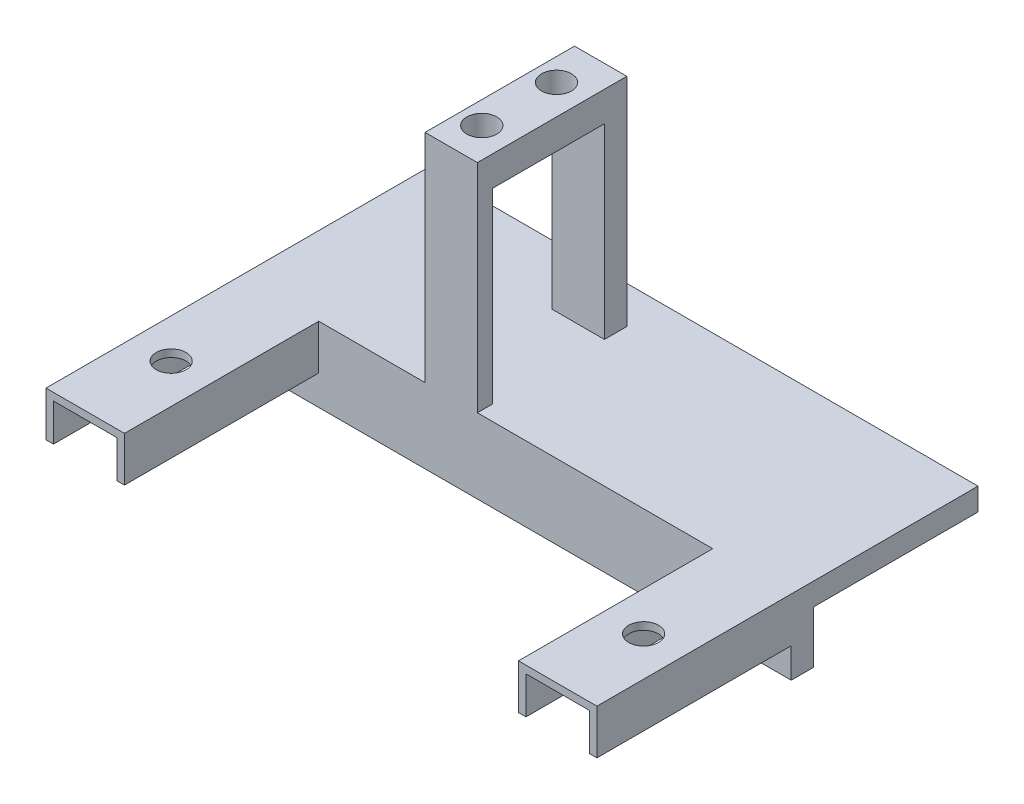
SolidWorks part; units mm, degrees
ref_plane "Front Plane" through (0, 0, 0) normal (0, 0, 1) x (1, 0, 0)
ref_plane "Top Plane" through (0, 0, 0) normal (0, 1, 0) x (1, 0, 0)
ref_plane "Right Plane" through (0, 0, 0) normal (1, 0, 0) x (0, 0, -1)
sketch "Sketch1" plane through (0, 0, 0) normal (0, 0, 1) x (1, 0, 0)
  line L1 (0, 0) -> (73.73, 0)
  line L2 (0, 0) -> (0, 10)
  line L3 (0, 10) -> (73.73, 10)
  line L4 (73.73, 0) -> (73.73, 10)
  dimension "D1" = 73.73
  dimension "D2" = 10
extrude "Boss-Extrude1" add sketch "Sketch1" along normal blind 3
sketch "Sketch2" plane through (0, 0, 3) normal (0, 0, 1) x (1, 0, 0)
  line L0 (0, 4) -> (0, 10)
  line L1 (0, 10) -> (0, 0) construction
  line L2 (0, 10) -> (10.5, 10)
  line L3 (73.73, 10) -> (0, 10) construction
  line L4 (10.5, 10) -> (10.5, 4)
  line L5 (10.5, 4) -> (9.5, 4)
  line L6 (9.5, 4) -> (9.5, 9)
  line L7 (9.5, 9) -> (1, 9)
  line L8 (1, 9) -> (1, 4)
  line L9 (1, 4) -> (0, 4)
  dimension "D1" = 1
  dimension "D2" = 1
  dimension "D3" = 6
  dimension "D4" = 6
  dimension "D5" = 1
  dimension "D6" = 10.5
extrude "Boss-Extrude2" add sketch "Sketch2" along normal blind 26
sketch "Sketch7" plane through (0, 0, 3) normal (0, 0, 1) x (1, 0, 0)
  line L0 (-2.8767, 4) -> (79.6378, 4) construction
  line L1 (73.73, 10) -> (73.73, 4)
  line L2 (73.73, 0) -> (73.73, 10) construction
  line L3 (73.73, 4) -> (72.73, 4)
  line L4 (72.73, 4) -> (72.73, 9)
  line L5 (72.73, 9) -> (64.23, 9)
  line L6 (64.23, 9) -> (64.23, 4)
  line L7 (64.23, 4) -> (63.23, 4)
  line L8 (63.23, 4) -> (63.23, 10)
  line L9 (73.73, 10) -> (10.5, 10) construction
  line L10 (63.23, 10) -> (73.73, 10)
  dimension "D1" = 1
  dimension "D2" = 1
  dimension "D3" = 1
  dimension "D4" = 10.5
extrude "Boss-Extrude3" add sketch "Sketch7" along normal blind 26
sketch "Sketch8" plane through (0, 10, 0) normal (0, 1, 0) x (1, 0, 0)
  line L0 (5.25, -29) -> (5.25, -34.0804) construction
  line L1 (10.5, -29) -> (0, -29) construction
  line L2 (5.25, -34.0804) -> (5.25, 6.4511) construction
  line L3 (68.48, -29) -> (68.48, -34.7376) construction
  line L4 (73.73, -29) -> (63.23, -29) construction
  line L5 (68.48, -34.7376) -> (68.48, 5.4901) construction
  circle A0 centre (5.25, -17.5) radius 2
  circle A1 centre (68.48, -17.5) radius 2
  dimension "D2" = 4
  dimension "D4" = 4
  dimension "D1" = 11.5
  dimension "D3" = 11.5
extrude "Cut-Extrude1" cut sketch "Sketch8" against normal through all
sketch "Sketch10" plane through (0, 0, 0) normal (0, 0, -1) x (-1, 0, 0)
  line L0 (0, 10) -> (0, 0) construction
  line L1 (-73.73, 10) -> (0, 10)
  line L2 (-73.73, 10) -> (-73.73, 7)
  line L3 (-73.73, 7) -> (0, 7)
  line L4 (0, 10) -> (0, 7)
  dimension "D1" = 3
extrude "Boss-Extrude4" add sketch "Sketch10" along normal blind 22
sketch "Sketch11" plane through (0, 10, 0) normal (0, 1, 0) x (1, 0, 0)
  line L0 (63.23, -3) -> (10.5, -3) construction
  line L1 (24.73, -3) -> (31.73, -3)
  line L2 (24.73, -3) -> (24.73, 17)
  line L3 (24.73, 17) -> (31.73, 17)
  line L4 (31.73, -3) -> (31.73, 17)
  line L5 (73.73, -29) -> (73.73, 22) construction
  dimension "D1" = 42
  dimension "D2" = 7
  dimension "D3" = 20
extrude "Boss-Extrude5" add sketch "Sketch11" along normal blind 29
sketch "Sketch12" plane through (0, 39, 0) normal (0, 1, 0) x (1, 0, 0)
  line L0 (27.73, 17) -> (27.73, 25.818) construction
  line L1 (31.73, 17) -> (24.73, 17) construction
  line L2 (27.73, 25.818) -> (27.73, -5.5567) construction
  line L3 (31.73, -3) -> (31.73, 17) construction
  line L4 (24.73, -3) -> (31.73, -3) construction
  circle A0 centre (27.73, 11.59) radius 2
  circle A1 centre (27.73, 1.59) radius 2
  dimension "D4" = 4
  dimension "D5" = 4
  dimension "D1" = 4
  dimension "D2" = 5.41
  dimension "D3" = 4.59
extrude "Cut-Extrude2" cut sketch "Sketch12" against normal blind 10
sketch "Sketch13" plane through (24.73, 0, 0) normal (-1, 0, 0) x (0, 0, 1)
  line L0 (-17, 10) -> (3, 10) construction
  line L1 (-14, 10) -> (1, 10)
  line L2 (-14, 10) -> (-14, 35)
  line L3 (-14, 35) -> (1, 35)
  line L4 (1, 10) -> (1, 35)
  line L5 (3, 39) -> (3, 10) construction
  line L6 (-17, 39) -> (-17, 10) construction
  line L7 (-17, 39) -> (3, 39) construction
  dimension "D1" = 2
  dimension "D2" = 3
  dimension "D3" = 4
extrude "Cut-Extrude3" cut sketch "Sketch13" against normal through all
